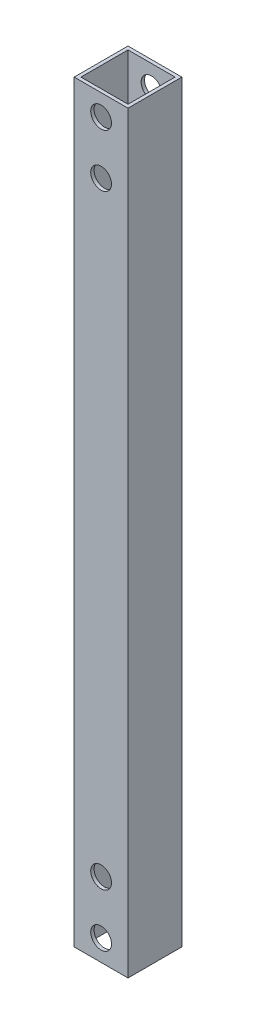
SolidWorks part; units mm, degrees
material "1060 Alloy"
ref_plane "Front Plane" through (0, 0, 0) normal (0, 0, 1) x (1, 0, 0)
ref_plane "Top Plane" through (0, 0, 0) normal (0, 1, 0) x (1, 0, 0)
ref_plane "Right Plane" through (0, 0, 0) normal (1, 0, 0) x (0, 0, -1)
sketch "Sketch1" plane through (0, 0, 0) normal (0, 1, 0) x (1, 0, 0)
  line L1 (-12.7, -12.7) -> (12.7, -12.7)
  line L2 (-12.7, -12.7) -> (-12.7, 12.7)
  line L3 (-12.7, 12.7) -> (12.7, 12.7)
  line L4 (12.7, -12.7) -> (12.7, 12.7)
  line L5 (-12.7, -12.7) -> (12.7, 12.7) construction
  line L6 (-12.7, 12.7) -> (12.7, -12.7) construction
  point P0 (0, 0)
  dimension "D1" = 25.4
extrude "Extrude-Thin1" add sketch "Sketch1" along normal blind 355.6 thin thin type one direction reverse wall 1.5875
sketch "Sketch2" plane through (0, 0, -12.7) normal (0, 0, -1) x (-1, 0, 0)
  line L0 (0, 355.6) -> (0, 0) construction
  line L1 (-12.7, 355.6) -> (12.7, 355.6) construction
  line L2 (-12.7, 0) -> (12.7, 0) construction
  line L3 (12.7, 177.8) -> (-12.7, 177.8) construction
  line L4 (12.7, 355.6) -> (12.7, 0) construction
  line L5 (-12.7, 355.6) -> (-12.7, 0) construction
  point P6 (0, 345.6)
  point P7 (0, 320.6)
  point P14 (0, 35)
  point P15 (0, 10)
  dimension "D1" = 10
  dimension "D2" = 25
hole_wizard "3/8 Clearance Hole1" positions "Sketch3" profile "Sketch4" hole size "3/8" standard "ANSI Inch" end condition through all
sketch "Sketch3" plane through (0, 0, -12.7) normal (0, 0, -1) x (-1, 0, 0)
  point P0 (0, 345.6)
  point P3 (0, 320.6)
  point P6 (0, 35)
  point P9 (0, 10)
sketch "Sketch4" plane through (0, 345.6, -12.7) normal (1, 0, 0) x (0, 1, 0)
  line L0 (0, 0) -> (0, 25.4)
  line L1 (0, 25.4) -> (4.9022, 25.4)
  line L2 (4.9022, 25.4) -> (4.9022, 0)
  line L5 (4.9022, 0) -> (0, 0)
  line L11 (0, -6.35) -> (0, 107.95) construction
  dimension "Thru Hole Dia." = 9.8044
  dimension "Thru Hole Depth" = 25.4
sketch "Sketch6" [suppressed] plane through (0, 0, -12.7) normal (0, 0, -1) x (-1, 0, 0)
  line L0 (12.7, 177.8) -> (-12.7, 177.8) construction
  line L1 (0, 355.6) -> (0, 0) construction
  point P0 (0, 190.3)
  point P1 (0, 165.3)
  dimension "D1" = 12.5
  dimension "D2" = 12.5
hole_wizard "M10 Clearance Hole2" [suppressed] positions "Sketch7" profile "Sketch8" hole size "M10" standard "ANSI Metric"
sketch "Sketch7" [suppressed] plane through (0, 0, -12.7) normal (0, 0, -1) x (-1, 0, 0)
  point P0 (0, 165.3)
  point P3 (0, 190.3)
sketch "Sketch8" plane through (0, 165.3, -12.7) normal (1, 0, 0) x (0, 1, 0)
  line L0 (0, 0) -> (0, 25.4)
  line L1 (0, 25.4) -> (5.5, 25.4)
  line L2 (5.5, 25.4) -> (5.5, 0.025)
  line L3 (5.5, 0.025) -> (5.525, 0)
  line L5 (5.525, 0) -> (0, 0)
  line L6 (-5.5, 0.025) -> (-5.525, 0) construction
  line L11 (0, -6.35) -> (0, 107.95) construction
  dimension "Thru Hole Dia." = 11
  dimension "Thru Hole Depth" = 25.4
  dimension "Near C'Sink Dia." = 11.05
  dimension "Near C'Sink Angle" = 90
pattern_linear "LPattern2" [suppressed] count 6 spacing 25 count 6 spacing 25
